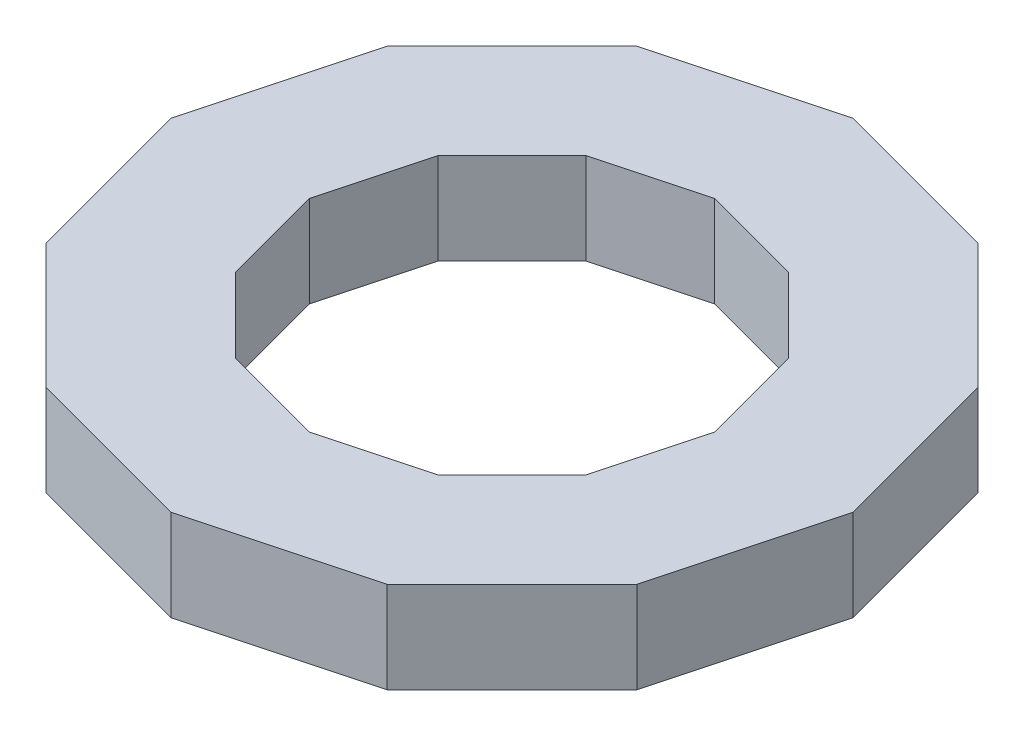
SolidWorks part; units mm, degrees
ref_plane "Front Plane" through (0, 0, 0) normal (0, 0, 1) x (1, 0, 0)
ref_plane "Top Plane" through (0, 0, 0) normal (0, 1, 0) x (1, 0, 0)
ref_plane "Right Plane" through (0, 0, 0) normal (1, 0, 0) x (0, 0, -1)
sketch "Sketch1" plane through (0, 0, 0) normal (0, 1, 0) x (1, 0, 0)
  line L0 (0, 0) -> (42.2245, 0) construction
  line L1 (42.2245, 0) -> (36.5675, 21.1122)
  line L2 (36.5675, 21.1122) -> (21.1122, 36.5675)
  line L3 (21.1122, 36.5675) -> (0, 42.2245)
  line L4 (0, 42.2245) -> (-21.1122, 36.5675)
  line L5 (-21.1122, 36.5675) -> (-36.5675, 21.1122)
  line L6 (-36.5675, 21.1122) -> (-42.2245, 0)
  line L7 (-42.2245, 0) -> (-36.5675, -21.1122)
  line L8 (-36.5675, -21.1122) -> (-21.1122, -36.5675)
  line L9 (-21.1122, -36.5675) -> (0, -42.2245)
  line L10 (0, -42.2245) -> (21.1122, -36.5675)
  line L11 (21.1122, -36.5675) -> (36.5675, -21.1122)
  line L12 (36.5675, -21.1122) -> (42.2245, 0)
  line L13 (71.1501, 0) -> (61.6178, 35.575)
  line L14 (61.6178, 35.575) -> (35.575, 61.6178)
  line L15 (35.575, 61.6178) -> (0, 71.1501)
  line L16 (0, 71.1501) -> (-35.575, 61.6178)
  line L17 (-35.575, 61.6178) -> (-61.6178, 35.575)
  line L18 (-61.6178, 35.575) -> (-71.1501, 0)
  line L19 (-71.1501, 0) -> (-61.6178, -35.575)
  line L20 (-61.6178, -35.575) -> (-35.575, -61.6178)
  line L21 (-35.575, -61.6178) -> (0, -71.1501)
  line L22 (0, -71.1501) -> (35.575, -61.6178)
  line L23 (35.575, -61.6178) -> (61.6178, -35.575)
  line L24 (61.6178, -35.575) -> (71.1501, 0)
  circle A0 centre (0, 0) radius 40.7857 construction
  circle A1 centre (0, 0) radius 68.7257 construction
  dimension "D1" = 27.94
  dimension "D2" = 36.83
  dimension "D3" = 68.7257
extrude "Boss-Extrude1" add sketch "Sketch1" along normal blind 19.05
